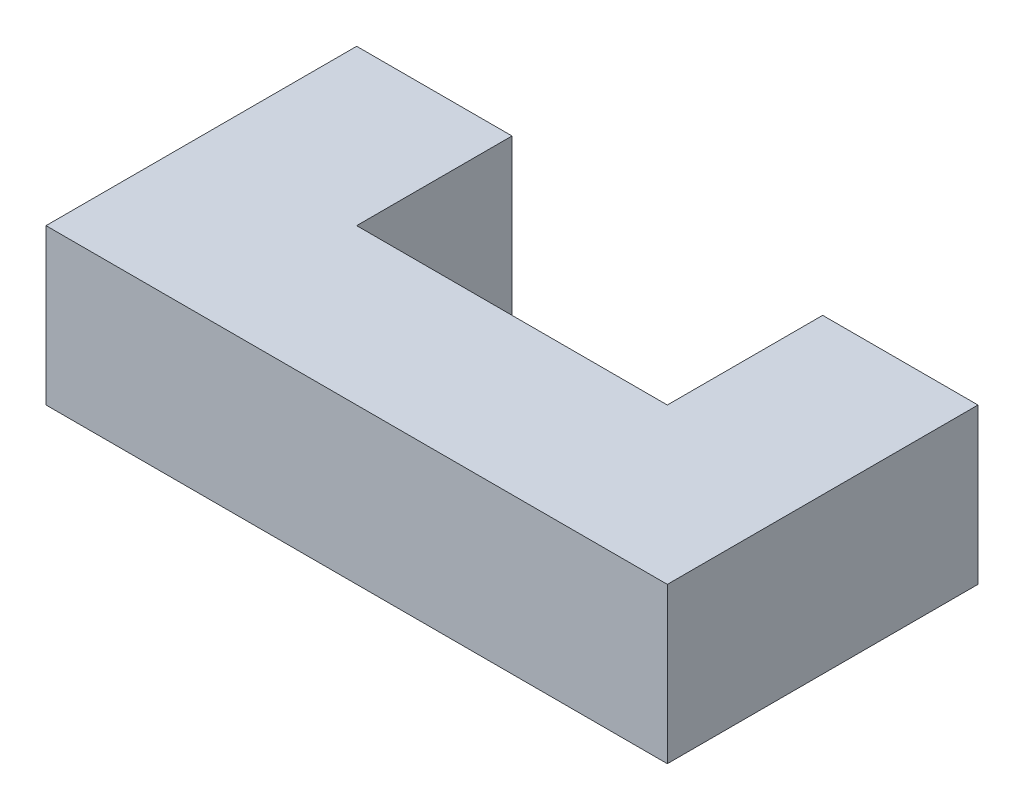
SolidWorks part; units mm, degrees
ref_plane "Front Plane" through (0, 0, 0) normal (0, 0, 1) x (1, 0, 0)
ref_plane "Top Plane" through (0, 0, 0) normal (0, 1, 0) x (1, 0, 0)
ref_plane "Right Plane" through (0, 0, 0) normal (1, 0, 0) x (0, 0, -1)
sketch "Sketch1" plane through (0, 0, 0) normal (0, 1, 0) x (1, 0, 0)
  line L0 (-5, 0) -> (-10, -5) construction
  line L1 (-10, -5) -> (10, -5)
  line L2 (-10, -5) -> (-10, 5)
  line L3 (-10, 5) -> (10, 5)
  line L4 (10, -5) -> (10, 5)
  line L5 (-10, -5) -> (10, 5) construction
  line L6 (-10, 5) -> (10, -5) construction
  line L7 (-5, 5) -> (5, 5)
  line L8 (-5, 5) -> (-5, 0)
  line L9 (-5, 0) -> (5, 0)
  line L10 (5, 5) -> (5, 0)
  line L11 (5, 0) -> (10, -5) construction
  point P0 (0, 0)
  point P14 (0, 0)
  point P15 (0, 0)
  dimension "D1" = 20
  dimension "D2" = 10
  dimension "D3" = 5
  dimension "D4" = 5
  dimension "D5" = 5
extrude "Boss-Extrude1" add sketch "Sketch1" along normal blind 5 contours L3 L10 L9 L8 L2 L1 L4
